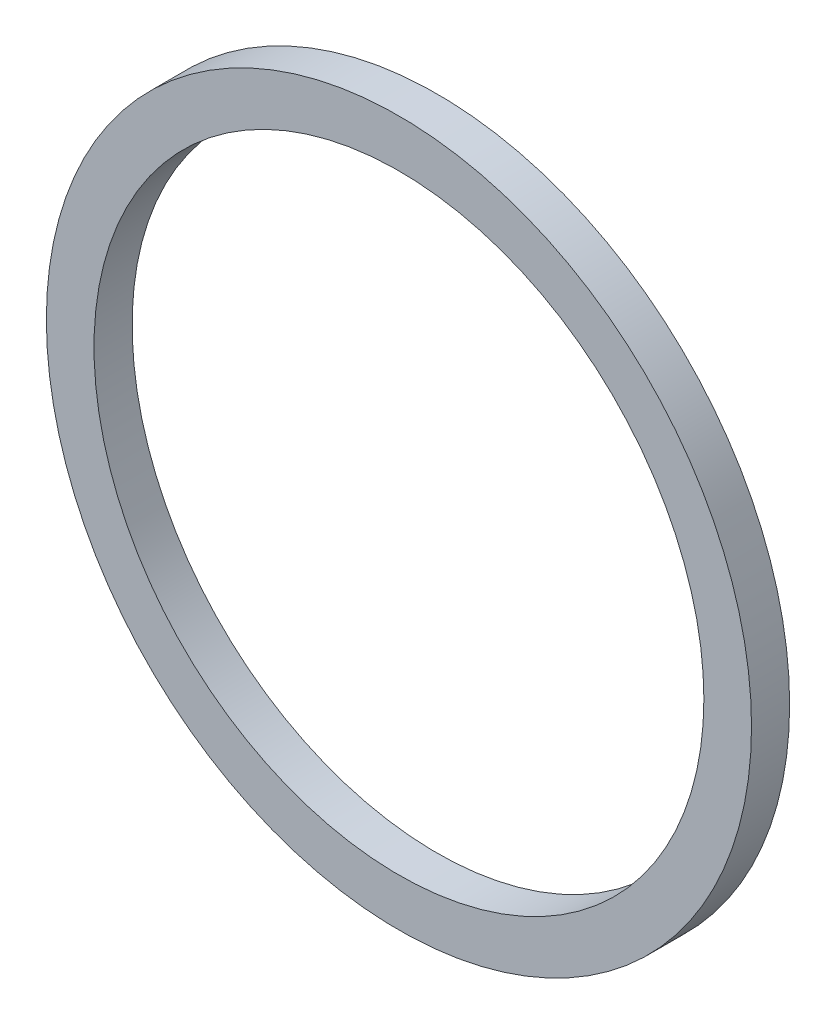
SolidWorks part; units mm, degrees
material "PETG"
ref_plane "前视基准面" through (0, 0, 0) normal (0, 0, 1) x (1, 0, 0)
ref_plane "上视基准面" through (0, 0, 0) normal (0, 1, 0) x (1, 0, 0)
ref_plane "右视基准面" through (0, 0, 0) normal (1, 0, 0) x (0, 0, -1)
other "Configuration Table"
sketch "草图1" plane through (0, 0, 0) normal (0, 0, 1) x (1, 0, 0)
  circle A0 centre (0, 0) radius 3.2
  circle A1 centre (0, 0) radius 3.7
  point P3 (0, 0)
  dimension "D1" = 6.4
  dimension "D2" = 7.4
extrude "凸台-拉伸1" add sketch "草图1" along normal blind 0.4
